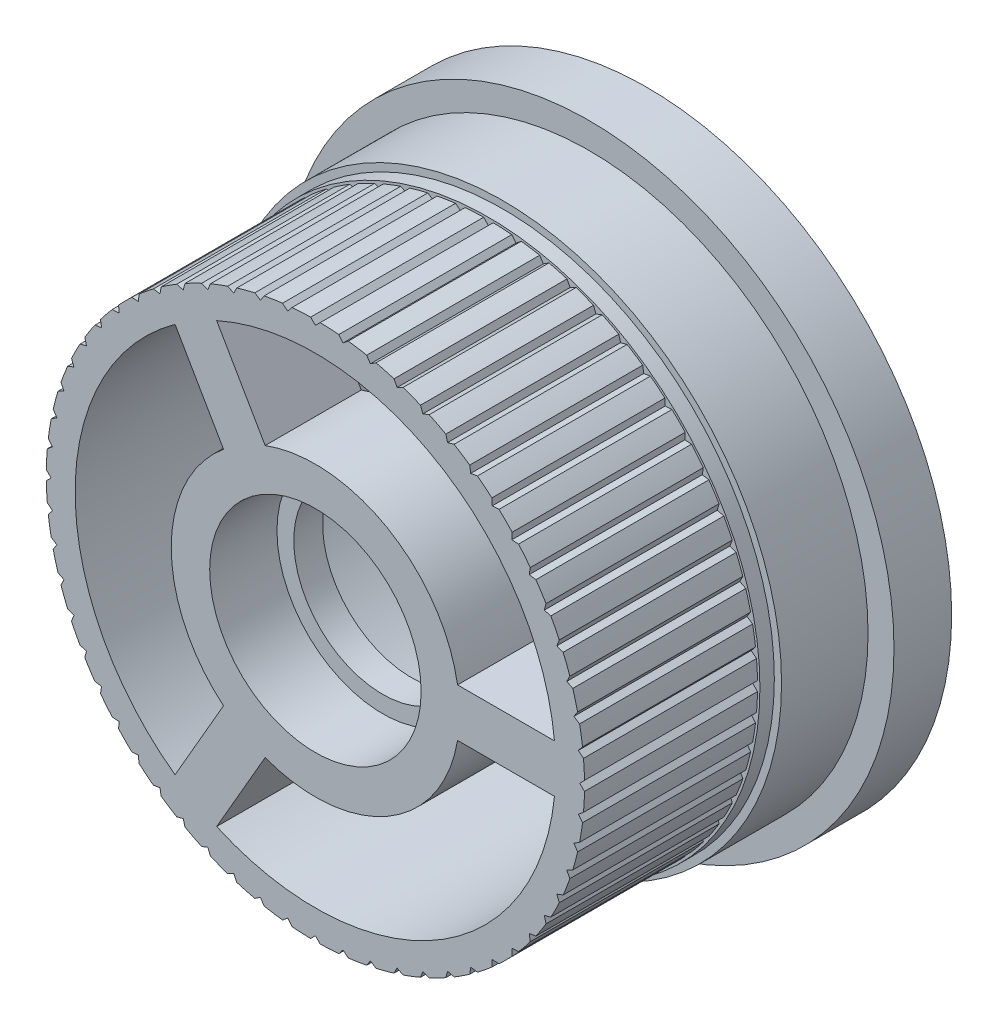
SolidWorks part; units mm, degrees
ref_plane "Front Plane" through (0, 0, 0) normal (0, 0, 1) x (1, 0, 0)
ref_plane "Top Plane" through (0, 0, 0) normal (0, 1, 0) x (1, 0, 0)
ref_plane "Right Plane" through (0, 0, 0) normal (1, 0, 0) x (0, 0, -1)
sketch "Sketch1" plane through (0, 0, 0) normal (0, 0, 1) x (1, 0, 0)
  circle A0 centre (0, 0) radius 31.7
extrude "Flange" add sketch "Sketch1" along normal blind 6
ref_plane "Plane_z6" through (0, 0, 6) normal (0, 0, 1) x (1, 0, 0)
sketch "Sketch2" plane through (0, 0, 6) normal (0, 0, 1) x (1, 0, 0)
  circle A0 centre (0, 0) radius 29
extrude "Thread" add sketch "Sketch2" along normal blind 9
ref_plane "Plane_z15" through (0, 0, 15) normal (0, 0, 1) x (1, 0, 0)
sketch "Sketch3" plane through (0, 0, 15) normal (0, 0, 1) x (1, 0, 0)
  circle A0 centre (0, 0) radius 28.25
extrude "Relief" add sketch "Sketch3" along normal blind 1.5
ref_plane "Plane_z16_5" through (0, 0, 16.5) normal (0, 0, 1) x (1, 0, 0)
sketch "Sketch4" plane through (0, 0, 16.5) normal (0, 0, 1) x (1, 0, 0)
  circle A0 centre (0, 0) radius 28
extrude "Pilot" add sketch "Sketch4" along normal blind 18
sketch "Sketch5" plane through (0, 0, 0) normal (0, 0, 1) x (1, 0, 0)
  circle A0 centre (0, 0) radius 25
extrude "Ring_bore" cut sketch "Sketch5" along normal blind 34.5
ref_plane "Plane_z24_5" through (0, 0, 24.5) normal (0, 0, 1) x (1, 0, 0)
sketch "Sketch6" plane through (0, 0, 24.5) normal (0, 0, 1) x (1, 0, 0)
  circle A0 centre (0, 0) radius 15
  circle A1 centre (0, 0) radius 9.25
extrude "Hub" add sketch "Sketch6" along normal blind 10
sketch "Sketch7" plane through (0, 0, 24.5) normal (0, 0, 1) x (1, 0, 0)
  line L0 (14, -2.5) -> (26, -2.5)
  line L1 (26, -2.5) -> (26, 2.5)
  line L2 (26, 2.5) -> (14, 2.5)
  line L3 (14, 2.5) -> (14, -2.5)
  line L4 (-4.8349, 13.3744) -> (-10.8349, 23.7667)
  line L5 (-10.8349, 23.7667) -> (-15.1651, 21.2667)
  line L6 (-15.1651, 21.2667) -> (-9.1651, 10.8744)
  line L7 (-9.1651, 10.8744) -> (-4.8349, 13.3744)
  line L8 (-9.1651, -10.8744) -> (-15.1651, -21.2667)
  line L9 (-15.1651, -21.2667) -> (-10.8349, -23.7667)
  line L10 (-10.8349, -23.7667) -> (-4.8349, -13.3744)
  line L11 (-4.8349, -13.3744) -> (-9.1651, -10.8744)
extrude "Spokes" add sketch "Sketch7" along normal blind 10
ref_plane "Plane_z27_5" through (0, 0, 27.5) normal (0, 0, 1) x (1, 0, 0)
sketch "Sketch8" plane through (0, 0, 27.5) normal (0, 0, 1) x (1, 0, 0)
  circle A0 centre (0, 0) radius 11
  circle A1 centre (0, 0) radius 9.25
extrude "Bearing_seat" cut sketch "Sketch8" along normal blind 7
sketch "Sketch9" plane through (0, 0, 16.5) normal (0, 0, 1) x (1, 0, 0)
  line L0 (27.5, 0) -> (29, 1.5)
  line L1 (29, 1.5) -> (29, -1.5)
  line L2 (29, -1.5) -> (27.5, 0)
  line L3 (27.3494, 2.8745) -> (28.6843, 4.5231)
  line L4 (28.6843, 4.5231) -> (28.9979, 1.5395)
  line L5 (28.9979, 1.5395) -> (27.3494, 2.8745)
  line L6 (26.8991, 5.7176) -> (28.0544, 7.4967)
  line L7 (28.0544, 7.4967) -> (28.6781, 4.5622)
  line L8 (28.6781, 4.5622) -> (26.8991, 5.7176)
  line L9 (26.1541, 8.498) -> (27.1171, 10.3881)
  line L10 (27.1171, 10.3881) -> (28.0442, 7.5349)
  line L11 (28.0442, 7.5349) -> (26.1541, 8.498)
  line L12 (25.1225, 11.1853) -> (25.8827, 13.1657)
  line L13 (25.8827, 13.1657) -> (27.1029, 10.425)
  line L14 (27.1029, 10.425) -> (25.1225, 11.1853)
  line L15 (23.8157, 13.75) -> (24.3647, 15.799)
  line L16 (24.3647, 15.799) -> (25.8647, 13.201)
  line L17 (25.8647, 13.201) -> (23.8157, 13.75)
  line L18 (22.248, 16.1641) -> (22.5798, 18.2593)
  line L19 (22.5798, 18.2593) -> (24.3432, 15.8322)
  line L20 (24.3432, 15.8322) -> (22.248, 16.1641)
  line L21 (20.4365, 18.4011) -> (20.5475, 20.5195)
  line L22 (20.5475, 20.5195) -> (22.5549, 18.2901)
  line L23 (22.5549, 18.2901) -> (20.4365, 18.4011)
  line L24 (18.4011, 20.4365) -> (18.2901, 22.5549)
  line L25 (18.2901, 22.5549) -> (20.5195, 20.5475)
  line L26 (20.5195, 20.5475) -> (18.4011, 20.4365)
  line L27 (16.1641, 22.248) -> (15.8322, 24.3432)
  line L28 (15.8322, 24.3432) -> (18.2593, 22.5798)
  line L29 (18.2593, 22.5798) -> (16.1641, 22.248)
  line L30 (13.75, 23.8157) -> (13.201, 25.8647)
  line L31 (13.201, 25.8647) -> (15.799, 24.3647)
  line L32 (15.799, 24.3647) -> (13.75, 23.8157)
  line L33 (11.1853, 25.1225) -> (10.425, 27.1029)
  line L34 (10.425, 27.1029) -> (13.1657, 25.8827)
  line L35 (13.1657, 25.8827) -> (11.1853, 25.1225)
  line L36 (8.498, 26.1541) -> (7.5349, 28.0442)
  line L37 (7.5349, 28.0442) -> (10.3881, 27.1171)
  line L38 (10.3881, 27.1171) -> (8.498, 26.1541)
  line L39 (5.7176, 26.8991) -> (4.5622, 28.6781)
  line L40 (4.5622, 28.6781) -> (7.4967, 28.0544)
  line L41 (7.4967, 28.0544) -> (5.7176, 26.8991)
  line L42 (2.8745, 27.3494) -> (1.5395, 28.9979)
  line L43 (1.5395, 28.9979) -> (4.5231, 28.6843)
  line L44 (4.5231, 28.6843) -> (2.8745, 27.3494)
  line L45 (0, 27.5) -> (-1.5, 29)
  line L46 (-1.5, 29) -> (1.5, 29)
  line L47 (1.5, 29) -> (0, 27.5)
  line L48 (-2.8745, 27.3494) -> (-4.5231, 28.6843)
  line L49 (-4.5231, 28.6843) -> (-1.5395, 28.9979)
  line L50 (-1.5395, 28.9979) -> (-2.8745, 27.3494)
  line L51 (-5.7176, 26.8991) -> (-7.4967, 28.0544)
  line L52 (-7.4967, 28.0544) -> (-4.5622, 28.6781)
  line L53 (-4.5622, 28.6781) -> (-5.7176, 26.8991)
  line L54 (-8.498, 26.1541) -> (-10.3881, 27.1171)
  line L55 (-10.3881, 27.1171) -> (-7.5349, 28.0442)
  line L56 (-7.5349, 28.0442) -> (-8.498, 26.1541)
  line L57 (-11.1853, 25.1225) -> (-13.1657, 25.8827)
  line L58 (-13.1657, 25.8827) -> (-10.425, 27.1029)
  line L59 (-10.425, 27.1029) -> (-11.1853, 25.1225)
  line L60 (-13.75, 23.8157) -> (-15.799, 24.3647)
  line L61 (-15.799, 24.3647) -> (-13.201, 25.8647)
  line L62 (-13.201, 25.8647) -> (-13.75, 23.8157)
  line L63 (-16.1641, 22.248) -> (-18.2593, 22.5798)
  line L64 (-18.2593, 22.5798) -> (-15.8322, 24.3432)
  line L65 (-15.8322, 24.3432) -> (-16.1641, 22.248)
  line L66 (-18.4011, 20.4365) -> (-20.5195, 20.5475)
  line L67 (-20.5195, 20.5475) -> (-18.2901, 22.5549)
  line L68 (-18.2901, 22.5549) -> (-18.4011, 20.4365)
  line L69 (-20.4365, 18.4011) -> (-22.5549, 18.2901)
  line L70 (-22.5549, 18.2901) -> (-20.5475, 20.5195)
  line L71 (-20.5475, 20.5195) -> (-20.4365, 18.4011)
  line L72 (-22.248, 16.1641) -> (-24.3432, 15.8322)
  line L73 (-24.3432, 15.8322) -> (-22.5798, 18.2593)
  line L74 (-22.5798, 18.2593) -> (-22.248, 16.1641)
  line L75 (-23.8157, 13.75) -> (-25.8647, 13.201)
  line L76 (-25.8647, 13.201) -> (-24.3647, 15.799)
  line L77 (-24.3647, 15.799) -> (-23.8157, 13.75)
  line L78 (-25.1225, 11.1853) -> (-27.1029, 10.425)
  line L79 (-27.1029, 10.425) -> (-25.8827, 13.1657)
  line L80 (-25.8827, 13.1657) -> (-25.1225, 11.1853)
  line L81 (-26.1541, 8.498) -> (-28.0442, 7.5349)
  line L82 (-28.0442, 7.5349) -> (-27.1171, 10.3881)
  line L83 (-27.1171, 10.3881) -> (-26.1541, 8.498)
  line L84 (-26.8991, 5.7176) -> (-28.6781, 4.5622)
  line L85 (-28.6781, 4.5622) -> (-28.0544, 7.4967)
  line L86 (-28.0544, 7.4967) -> (-26.8991, 5.7176)
  line L87 (-27.3494, 2.8745) -> (-28.9979, 1.5395)
  line L88 (-28.9979, 1.5395) -> (-28.6843, 4.5231)
  line L89 (-28.6843, 4.5231) -> (-27.3494, 2.8745)
  line L90 (-27.5, 0) -> (-29, -1.5)
  line L91 (-29, -1.5) -> (-29, 1.5)
  line L92 (-29, 1.5) -> (-27.5, 0)
  line L93 (-27.3494, -2.8745) -> (-28.6843, -4.5231)
  line L94 (-28.6843, -4.5231) -> (-28.9979, -1.5395)
  line L95 (-28.9979, -1.5395) -> (-27.3494, -2.8745)
  line L96 (-26.8991, -5.7176) -> (-28.0544, -7.4967)
  line L97 (-28.0544, -7.4967) -> (-28.6781, -4.5622)
  line L98 (-28.6781, -4.5622) -> (-26.8991, -5.7176)
  line L99 (-26.1541, -8.498) -> (-27.1171, -10.3881)
  line L100 (-27.1171, -10.3881) -> (-28.0442, -7.5349)
  line L101 (-28.0442, -7.5349) -> (-26.1541, -8.498)
  line L102 (-25.1225, -11.1853) -> (-25.8827, -13.1657)
  line L103 (-25.8827, -13.1657) -> (-27.1029, -10.425)
  line L104 (-27.1029, -10.425) -> (-25.1225, -11.1853)
  line L105 (-23.8157, -13.75) -> (-24.3647, -15.799)
  line L106 (-24.3647, -15.799) -> (-25.8647, -13.201)
  line L107 (-25.8647, -13.201) -> (-23.8157, -13.75)
  line L108 (-22.248, -16.1641) -> (-22.5798, -18.2593)
  line L109 (-22.5798, -18.2593) -> (-24.3432, -15.8322)
  line L110 (-24.3432, -15.8322) -> (-22.248, -16.1641)
  line L111 (-20.4365, -18.4011) -> (-20.5475, -20.5195)
  line L112 (-20.5475, -20.5195) -> (-22.5549, -18.2901)
  line L113 (-22.5549, -18.2901) -> (-20.4365, -18.4011)
  line L114 (-18.4011, -20.4365) -> (-18.2901, -22.5549)
  line L115 (-18.2901, -22.5549) -> (-20.5195, -20.5475)
  line L116 (-20.5195, -20.5475) -> (-18.4011, -20.4365)
  line L117 (-16.1641, -22.248) -> (-15.8322, -24.3432)
  line L118 (-15.8322, -24.3432) -> (-18.2593, -22.5798)
  line L119 (-18.2593, -22.5798) -> (-16.1641, -22.248)
  line L120 (-13.75, -23.8157) -> (-13.201, -25.8647)
  line L121 (-13.201, -25.8647) -> (-15.799, -24.3647)
  line L122 (-15.799, -24.3647) -> (-13.75, -23.8157)
  line L123 (-11.1853, -25.1225) -> (-10.425, -27.1029)
  line L124 (-10.425, -27.1029) -> (-13.1657, -25.8827)
  line L125 (-13.1657, -25.8827) -> (-11.1853, -25.1225)
  line L126 (-8.498, -26.1541) -> (-7.5349, -28.0442)
  line L127 (-7.5349, -28.0442) -> (-10.3881, -27.1171)
  line L128 (-10.3881, -27.1171) -> (-8.498, -26.1541)
  line L129 (-5.7176, -26.8991) -> (-4.5622, -28.6781)
  line L130 (-4.5622, -28.6781) -> (-7.4967, -28.0544)
  line L131 (-7.4967, -28.0544) -> (-5.7176, -26.8991)
  line L132 (-2.8745, -27.3494) -> (-1.5395, -28.9979)
  line L133 (-1.5395, -28.9979) -> (-4.5231, -28.6843)
  line L134 (-4.5231, -28.6843) -> (-2.8745, -27.3494)
  line L135 (0, -27.5) -> (1.5, -29)
  line L136 (1.5, -29) -> (-1.5, -29)
  line L137 (-1.5, -29) -> (0, -27.5)
  line L138 (2.8745, -27.3494) -> (4.5231, -28.6843)
  line L139 (4.5231, -28.6843) -> (1.5395, -28.9979)
  line L140 (1.5395, -28.9979) -> (2.8745, -27.3494)
  line L141 (5.7176, -26.8991) -> (7.4967, -28.0544)
  line L142 (7.4967, -28.0544) -> (4.5622, -28.6781)
  line L143 (4.5622, -28.6781) -> (5.7176, -26.8991)
  line L144 (8.498, -26.1541) -> (10.3881, -27.1171)
  line L145 (10.3881, -27.1171) -> (7.5349, -28.0442)
  line L146 (7.5349, -28.0442) -> (8.498, -26.1541)
  line L147 (11.1853, -25.1225) -> (13.1657, -25.8827)
  line L148 (13.1657, -25.8827) -> (10.425, -27.1029)
  line L149 (10.425, -27.1029) -> (11.1853, -25.1225)
  line L150 (13.75, -23.8157) -> (15.799, -24.3647)
  line L151 (15.799, -24.3647) -> (13.201, -25.8647)
  line L152 (13.201, -25.8647) -> (13.75, -23.8157)
  line L153 (16.1641, -22.248) -> (18.2593, -22.5798)
  line L154 (18.2593, -22.5798) -> (15.8322, -24.3432)
  line L155 (15.8322, -24.3432) -> (16.1641, -22.248)
  line L156 (18.4011, -20.4365) -> (20.5195, -20.5475)
  line L157 (20.5195, -20.5475) -> (18.2901, -22.5549)
  line L158 (18.2901, -22.5549) -> (18.4011, -20.4365)
  line L159 (20.4365, -18.4011) -> (22.5549, -18.2901)
  line L160 (22.5549, -18.2901) -> (20.5475, -20.5195)
  line L161 (20.5475, -20.5195) -> (20.4365, -18.4011)
  line L162 (22.248, -16.1641) -> (24.3432, -15.8322)
  line L163 (24.3432, -15.8322) -> (22.5798, -18.2593)
  line L164 (22.5798, -18.2593) -> (22.248, -16.1641)
  line L165 (23.8157, -13.75) -> (25.8647, -13.201)
  line L166 (25.8647, -13.201) -> (24.3647, -15.799)
  line L167 (24.3647, -15.799) -> (23.8157, -13.75)
  line L168 (25.1225, -11.1853) -> (27.1029, -10.425)
  line L169 (27.1029, -10.425) -> (25.8827, -13.1657)
  line L170 (25.8827, -13.1657) -> (25.1225, -11.1853)
  line L171 (26.1541, -8.498) -> (28.0442, -7.5349)
  line L172 (28.0442, -7.5349) -> (27.1171, -10.3881)
  line L173 (27.1171, -10.3881) -> (26.1541, -8.498)
  line L174 (26.8991, -5.7176) -> (28.6781, -4.5622)
  line L175 (28.6781, -4.5622) -> (28.0544, -7.4967)
  line L176 (28.0544, -7.4967) -> (26.8991, -5.7176)
  line L177 (27.3494, -2.8745) -> (28.9979, -1.5395)
  line L178 (28.9979, -1.5395) -> (28.6843, -4.5231)
  line L179 (28.6843, -4.5231) -> (27.3494, -2.8745)
extrude "Click_grooves" cut sketch "Sketch9" along normal blind 18
